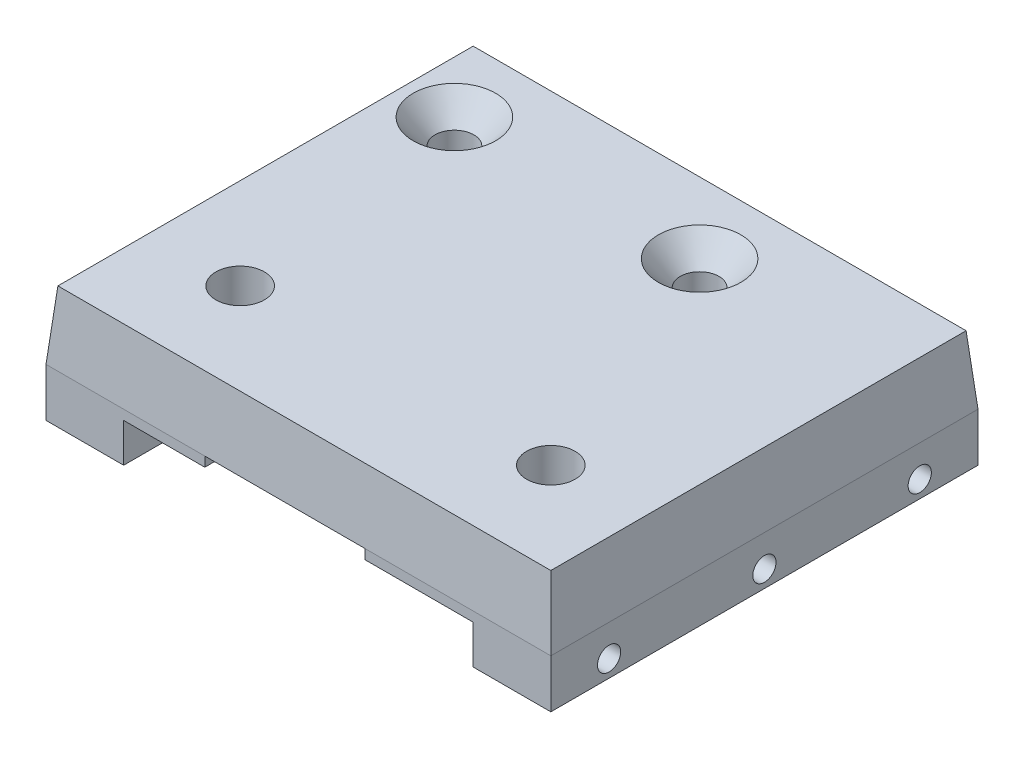
SolidWorks part; units mm, degrees
material "6061 Alloy"
ref_plane "Front Plane" through (0, 0, 0) normal (0, 0, 1) x (1, 0, 0)
ref_plane "Top Plane" through (0, 0, 0) normal (0, 1, 0) x (1, 0, 0)
ref_plane "Right Plane" through (0, 0, 0) normal (1, 0, 0) x (0, 0, -1)
sketch "Sketch1" plane through (0, 0, 0) normal (0, 1, 0) x (1, 0, 0)
  line L1 (41.275, -34.925) -> (-41.275, -34.925)
  line L2 (41.275, -34.925) -> (41.275, 34.925)
  line L3 (41.275, 34.925) -> (-41.275, 34.925)
  line L4 (-41.275, -34.925) -> (-41.275, 34.925)
  line L5 (41.275, -34.925) -> (-41.275, 34.925) construction
  line L6 (41.275, 34.925) -> (-41.275, -34.925) construction
  line L7 (-22.225, 34.925) -> (28.575, 34.925)
  line L8 (-22.225, 34.925) -> (-22.225, 92.075)
  line L9 (-22.225, 92.075) -> (28.575, 92.075)
  line L10 (28.575, 34.925) -> (28.575, 92.075)
  point P0 (0, 0)
  dimension "D1" = 82.55
  dimension "D2" = 69.85
  dimension "D3" = 12.7
  dimension "D4" = 19.05
  dimension "D5" = 50.8
  dimension "D6" = 127
extrude "Boss-Extrude1" add sketch "Sketch1" along normal blind 7.9375 contours L4 L1 L2 L3
sketch "Sketch2" plane through (0, 7.9375, 0) normal (0, 1, 0) x (1, 0, 0)
  line L1 (-41.275, -34.925) -> (41.275, -34.925)
  line L2 (-41.275, -34.925) -> (-41.275, 34.925)
  line L3 (-41.275, 34.925) -> (41.275, 34.925)
  line L4 (41.275, -34.925) -> (41.275, 34.925)
extrude "Boss-Extrude2" add sketch "Sketch2" along normal blind 3.175
hole_wizard "3/8-16 Tapped Hole1" positions "Sketch10" profile "Sketch11" tap size "3/8-16" standard "ANSI Inch"
sketch "Sketch10" plane through (0, 11.1125, 0) normal (0, 1, 0) x (1, 0, 0)
  line L0 (-41.275, 34.925) -> (-41.275, -34.925) construction
  line L1 (-41.275, -34.925) -> (41.275, -34.925) construction
  line L2 (41.275, -34.925) -> (41.275, 34.925) construction
  point P0 (-25.4, -19.05)
  point P2 (25.4, -19.05)
  dimension "D1" = 15.875
  dimension "D2" = 15.875
  dimension "D3" = 15.875
  dimension "D4" = 15.875
sketch "Sketch11" plane through (-25.4, 11.1125, 19.05) normal (1, 0, 0) x (0, 0, 1)
  line L0 (0, 0) -> (0, 11.9097)
  line L1 (0, 11.9097) -> (3.9687, 9.525)
  line L2 (3.9687, 9.525) -> (3.9687, 0)
  line L5 (3.9687, 0) -> (0, 0)
  line L10 (0, 11.9097) -> (-3.9688, 9.525) construction
  line L11 (0, -6.35) -> (0, 107.95) construction
  dimension "Tap Drill Dia." = 7.9375
  dimension "Tap Drill Depth" = 9.525
  dimension "Drill Angle" = 118
cosmetic thread "Hole Thread4" parameters "D1"=19.05, "D2"=9.525
cosmetic thread "Hole Thread5" parameters "D1"=19.05, "D2"=9.525
draft "Draft1" type of draft neutral plane draft angle 5 neutral plane "Top Plane" faces to draft 4 face at (0, 5.5563, -34.925) face at (-41.275, 5.5563, 0) face at (0, 5.5563, 34.925) face at (41.275, 5.5563, 0) neutral plane through (0, 0, 0) neutral plane normal (0, 1, 0) parameters "D1"=5
sketch "Sketch3" plane through (0, 0, 0) normal (0, -1, 0) x (1, 0, 0)
  line L7 (41.275, 34.925) -> (28.575, 34.925)
  line L8 (41.275, 34.925) -> (41.275, -34.925)
  line L9 (41.275, -34.925) -> (28.575, -34.925)
  line L10 (28.575, 34.925) -> (28.575, -34.925)
  line L13 (-41.275, -34.925) -> (-28.575, -34.925)
  line L14 (-41.275, -34.925) -> (-41.275, 34.925)
  line L15 (-41.275, 34.925) -> (-28.575, 34.925)
  line L16 (-28.575, -34.925) -> (-28.575, 34.925)
  dimension "D1" = 12.7
  dimension "D2" = 12.7
extrude "Boss-Extrude3" add sketch "Sketch3" along normal blind 7.9375
sketch "Sketch4" plane through (0, 0, 0) normal (0, -1, 0) x (1, 0, 0)
  line L1 (-28.575, 34.925) -> (-15.3077, 34.925)
  line L2 (-28.575, 34.925) -> (-28.575, -34.925)
  line L3 (-28.575, -34.925) -> (-15.3077, -34.925)
  line L4 (-15.3077, 34.925) -> (-15.3077, -34.925)
  line L6 (28.575, 34.925) -> (10.8909, 34.925)
  line L7 (28.575, 34.925) -> (28.575, -34.925)
  line L8 (28.575, -34.925) -> (10.8909, -34.925)
  line L9 (10.8909, 34.925) -> (10.8909, -34.925)
extrude "Wear Pads" add sketch "Sketch4" along normal blind 1.5875
hole_wizard "#10-24 Tapped Hole1" positions "Sketch5" profile "Sketch6" tap size "#10-24" standard "ANSI Inch"
sketch "Sketch5" plane through (41.275, 0, 0) normal (1, 0, 0) x (0, 0, -1)
  line L6 (-34.925, -5.1516) -> (34.925, -5.1516) construction
  line L8 (-34.925, -7.9375) -> (-34.925, 0) construction
  line L9 (34.925, -7.9375) -> (34.925, 0) construction
  point P0 (-25.4, -5.1516)
  point P2 (25.4, -5.1516)
  point P29 (0, -5.1516)
  dimension "D1" = 9.525
  dimension "D2" = 9.525
sketch "Sketch6" plane through (41.275, -5.1516, 25.4) normal (0, 1, 0) x (0, 0, -1)
  line L0 (0, 0) -> (0, 12.7)
  line L1 (0, 12.7) -> (1.8986, 12.7)
  line L2 (1.8986, 12.7) -> (1.8986, 0)
  line L5 (1.8986, 0) -> (0, 0)
  line L11 (0, -6.35) -> (0, 107.95) construction
  dimension "Thru Tap Drill Dia." = 3.7973
  dimension "Thru Tap Drill Depth" = 12.7
cosmetic thread "Hole Thread1" parameters "D2"=4.826
cosmetic thread "Hole Thread2" parameters "D2"=4.826
cosmetic thread "Hole Thread3" parameters "D2"=4.826
hole_wizard "1/4 (0.25) Diameter Hole1" positions "Sketch16" profile "Sketch17" hole size "1/4" standard "ANSI Inch"
sketch "Sketch16" plane through (0, 11.1125, 0) normal (0, 1, 0) x (1, 0, 0)
  point P0 (-31.7954, 22.3789)
  point P13 (8.3004, 22.3789)
sketch "Sketch17" plane through (-31.7954, 11.1125, -22.3789) normal (1, 0, 0) x (0, 0, 1)
  line L0 (0, 0) -> (0, 10.7977)
  line L1 (0, 10.7977) -> (3.175, 8.89)
  line L2 (3.175, 8.89) -> (3.175, 4.1053)
  line L3 (3.175, 4.1053) -> (6.7437, 0)
  line L5 (6.7437, 0) -> (0, 0)
  line L6 (-3.175, 4.1053) -> (-6.7437, 0) construction
  line L10 (0, 10.7977) -> (-3.175, 8.89) construction
  line L11 (0, -6.35) -> (0, 107.95) construction
  dimension "Hole Dia." = 6.35
  dimension "Hole Depth" = 8.89
  dimension "Near C'Sink Dia." = 13.4874
  dimension "Near C'Sink Angle" = 82
  dimension "Drill Angle" = 118
hole_wizard "1/4-20 Tapped Hole1" positions "Sketch18" profile "Sketch19" tap size "1/4-20" standard "ANSI Inch"
sketch "Sketch18" plane through (0, -7.9375, 0) normal (0, -1, 0) x (-1, 0, 0)
  point P0 (-33.3375, 15.875)
  point P3 (-33.3375, -15.875)
sketch "Sketch19" plane through (33.3375, -7.9375, -15.875) normal (1, 0, 0) x (0, 0, -1)
  line L0 (0, 0) -> (0, 12.9638)
  line L1 (0, 12.9638) -> (2.5527, 11.43)
  line L2 (2.5527, 11.43) -> (2.5527, 0)
  line L5 (2.5527, 0) -> (0, 0)
  line L10 (0, 12.9638) -> (-2.5527, 11.43) construction
  line L11 (0, -6.35) -> (0, 107.95) construction
  dimension "Tap Drill Dia." = 5.1054
  dimension "Tap Drill Depth" = 11.43
  dimension "Drill Angle" = 118
cosmetic thread "Hole Thread6" parameters "D1"=12.7, "D2"=6.35
cosmetic thread "Hole Thread7" parameters "D1"=12.7, "D2"=6.35
hole_wizard "1/4-20 Tapped Hole2" positions "Sketch20" profile "Sketch21" tap size "1/4-20" standard "ANSI Inch"
sketch "Sketch20" plane through (0, -7.9375, 0) normal (0, -1, 0) x (-1, 0, 0)
  point P0 (33.3375, -15.875)
  point P3 (33.3375, 15.875)
sketch "Sketch21" plane through (-33.3375, -7.9375, 15.875) normal (1, 0, 0) x (0, 0, -1)
  line L0 (0, 0) -> (0, 12.9638)
  line L1 (0, 12.9638) -> (2.5527, 11.43)
  line L2 (2.5527, 11.43) -> (2.5527, 0)
  line L5 (2.5527, 0) -> (0, 0)
  line L10 (0, 12.9638) -> (-2.5527, 11.43) construction
  line L11 (0, -6.35) -> (0, 107.95) construction
  dimension "Tap Drill Dia." = 5.1054
  dimension "Tap Drill Depth" = 11.43
  dimension "Drill Angle" = 118
cosmetic thread "Hole Thread8" parameters "D1"=12.7, "D2"=6.35
cosmetic thread "Hole Thread9" parameters "D1"=12.7, "D2"=6.35
